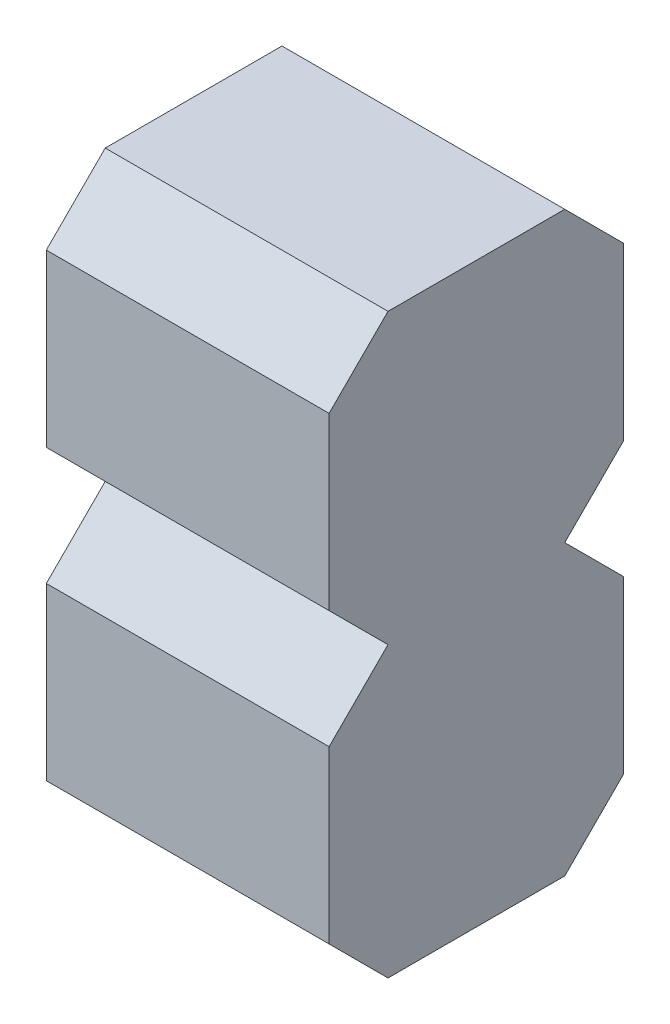
SolidWorks part; units mm, degrees
ref_plane "Přední rovina" through (0, 0, 0) normal (0, 0, 1) x (1, 0, 0)
ref_plane "Horní rovina" through (0, 0, 0) normal (0, 1, 0) x (1, 0, 0)
ref_plane "Pravá rovina" through (0, 0, 0) normal (1, 0, 0) x (0, 0, -1)
sketch "Skica1" plane through (0, 0, 0) normal (0, 0, 1) x (1, 0, 0)
  line L0 (0, 0) -> (-2.2149, 0) construction
  line L2 (0, 0) -> (-2.4, 0)
  line L3 (0, 0) -> (0, 4.9)
  line L4 (0, 4.9) -> (-2.4, 4.9)
  line L5 (-2.4, 0) -> (-2.4, 4.9)
  dimension "D1" = 2.4
  dimension "D2" = 4.9
extrude "Přidat vysunutím1" add sketch "Skica1" along normal blind 2.5
sketch "Skica3" plane through (0, 0, 0) normal (1, 0, 0) x (0, 0, -1)
  line L0 (-2.5, 2.45) -> (0, 2.45) construction
  line L1 (-2.5, 0) -> (-2.5, 4.9) construction
  line L2 (0, 0) -> (0, 4.9) construction
  line L3 (-2.5, 2.95) -> (-2, 2.45)
  line L4 (-2, 2.45) -> (-2.5, 1.95)
  line L5 (-2.5, 1.95) -> (-2.5, 2.95)
  line L6 (0, 2.95) -> (-0.5, 2.45)
  line L7 (-0.5, 2.45) -> (0, 1.95)
  line L8 (0, 1.95) -> (0, 2.95)
  line L9 (-2, 4.9) -> (-2.5, 4.4)
  line L10 (-2.5, 4.9) -> (0, 4.9) construction
  line L11 (-2.5, 4.4) -> (-2.5, 4.9)
  line L12 (-2.5, 4.9) -> (-2, 4.9)
  line L13 (-2.5, 0.5) -> (-2, 0)
  line L14 (-2.5, 0) -> (0, 0) construction
  line L15 (-2, 0) -> (-2.5, 0)
  line L16 (-2.5, 0) -> (-2.5, 0.5)
  line L17 (-0.5, 0) -> (0, 0.5)
  line L18 (0, 0.5) -> (0, 0)
  line L19 (0, 0) -> (-0.5, 0)
  line L20 (0, 4.9) -> (0, 4.4)
  line L21 (0, 4.4) -> (-0.5, 4.9)
  line L22 (-0.5, 4.9) -> (0, 4.9)
  dimension "D1" = 1
  dimension "D2" = 0.5
  dimension "D3" = 0.5
  dimension "D4" = 45
  dimension "D5" = 45
  dimension "D6" = 0.5
  dimension "D7" = 0.5
  dimension "D8" = 45
  dimension "D9" = 45
extrude "Odebrat vysunutím1" cut sketch "Skica3" against normal blind 2.5
